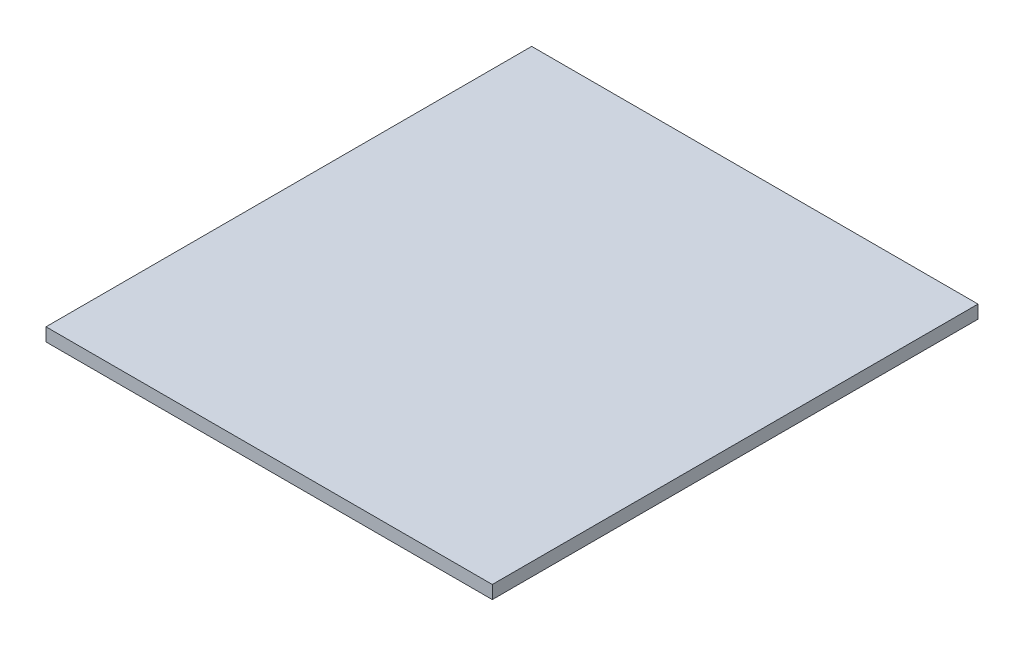
SolidWorks part; units mm, degrees
ref_plane "Front" through (0, 0, 0) normal (0, 0, 1) x (1, 0, 0)
ref_plane "Top" through (0, 0, 0) normal (0, 1, 0) x (1, 0, 0)
ref_plane "Right" through (0, 0, 0) normal (1, 0, 0) x (0, 0, -1)
sketch "Sketch1" plane through (0, 0, 0) normal (0, 1, 0) x (1, 0, 0)
  line L1 (-75, -75) -> (75, -75)
  line L2 (-75, -75) -> (-75, 75)
  line L3 (-75, 75) -> (75, 75)
  line L4 (75, -75) -> (75, 75)
  line L5 (-75, -75) -> (75, 75) construction
  line L6 (-75, 75) -> (75, -75) construction
  point P0 (0, 0)
  dimension "D1" = 150
  dimension "D2" = 150
extrude "Boss-Extrude1" add sketch "Sketch1" along normal blind 3
sketch "Sketch2" plane through (0, 3, 0) normal (0, 1, 0) x (1, 0, 0)
  line L0 (-50, -75) -> (-50, 36)
  line L1 (-75, -75) -> (75, -75) construction
  line L2 (-50, 36) -> (52, 36)
  line L3 (52, 36) -> (52, -75)
  line L4 (52, -75) -> (75, -75)
  line L5 (75, -75) -> (75, 75)
  line L6 (75, 75) -> (-75, 75)
  line L7 (-75, 75) -> (-75, -75)
  line L8 (-75, -75) -> (-50, -75)
  dimension "D1" = 111
  dimension "D2" = 23
  dimension "D3" = 25
extrude "Cut-Extrude1" cut sketch "Sketch2" against normal blind 10
